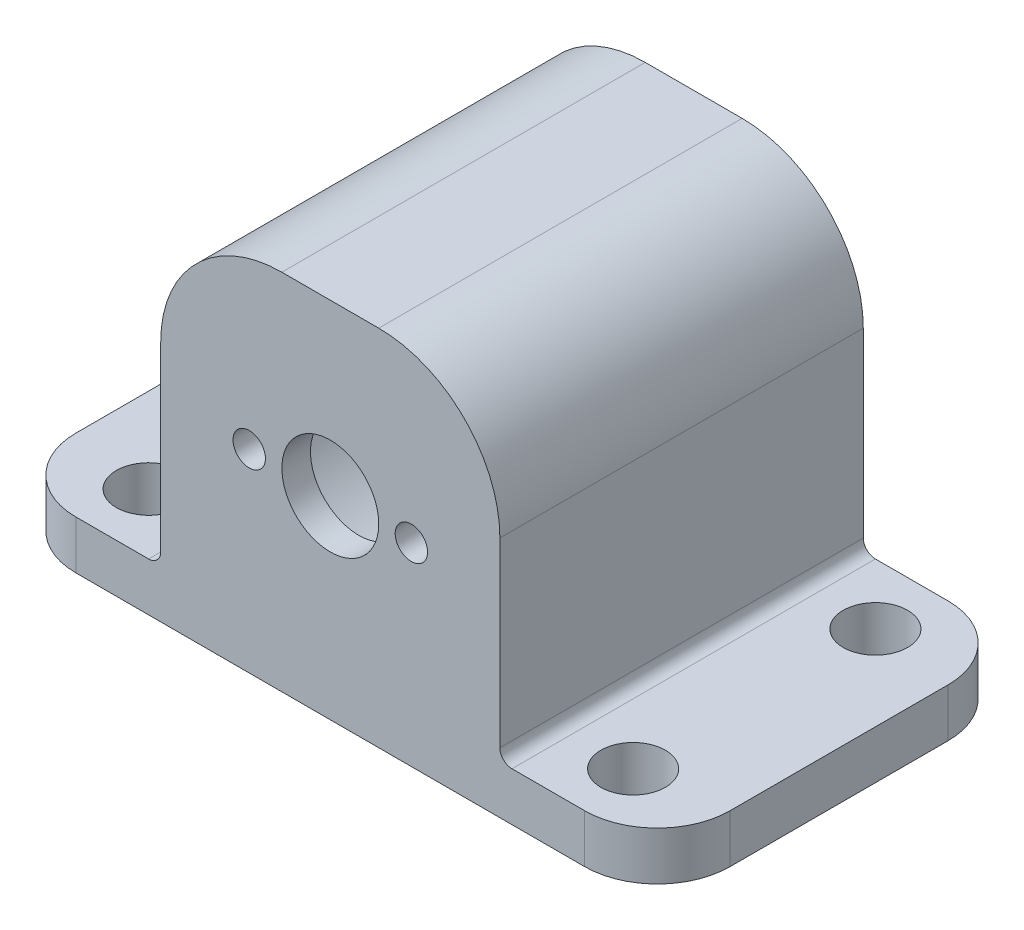
SolidWorks part; units mm, degrees
ref_plane "Front Plane" through (0, 0, 0) normal (0, 0, 1) x (1, 0, 0)
ref_plane "Top Plane" through (0, 0, 0) normal (0, 1, 0) x (1, 0, 0)
ref_plane "Right Plane" through (0, 0, 0) normal (1, 0, 0) x (0, 0, -1)
sketch "Sketch1" plane through (0, 0, 0) normal (0, 0, 1) x (1, 0, 0)
  line L0 (-34.29, 0) -> (34.29, 0)
  line L1 (34.29, 0) -> (34.29, 5.08)
  line L2 (34.29, 5.08) -> (19.05, 5.08)
  line L3 (17.78, 6.35) -> (17.78, 20.32)
  line L5 (0, 6.35) -> (0, 0)
  line L6 (-34.29, 5.08) -> (-19.05, 5.08)
  line L7 (-34.29, 0) -> (-34.29, 5.08)
  line L9 (-17.78, 6.35) -> (-17.78, 20.32)
  line L12 (-17.78, 20.32) -> (-17.78, 25.4)
  line L13 (-5.08, 38.1) -> (5.08, 38.1)
  line L14 (17.78, 20.32) -> (17.78, 25.4)
  arc A0 (-14.224, 20.32) -> (14.224, 20.32) centre (0, 20.32) ccw
  circle A1 centre (0, 20.32) radius 14.224
  arc A2 (-5.08, 38.1) -> (-17.78, 25.4) centre (-5.08, 25.4) ccw
  arc A3 (17.78, 25.4) -> (5.08, 38.1) centre (5.08, 25.4) ccw
  arc A4 (19.05, 5.08) -> (17.78, 6.35) centre (19.05, 6.35) cw
  arc A5 (-19.05, 5.08) -> (-17.78, 6.35) centre (-19.05, 6.35) ccw
  point P23 (17.78, 5.08)
  point P26 (-17.78, 5.08)
  dimension "D3" = 28.448
  dimension "D6" = 38.1
  dimension "D7" = 12.7
  dimension "D8" = 12.7
  dimension "D9" = 1.27
  dimension "D1" = 34.29
  dimension "D2" = 5.08
  dimension "D4" = 20.32
  dimension "D5" = 17.78
extrude "Boss-Extrude1" add sketch "Sketch1" along normal blind 38.1 contours A0 A1 | L9 L12 A2 L13 A3 L14 L3 A4 L2 L1 L0 L7 L6 A5
hole_wizard "1/4 Clearance Hole1" positions "Sketch2" profile "Sketch3" hole size "1/4" standard "ANSI Inch" end condition through all
sketch "Sketch2" plane through (0, 5.08, 0) normal (0, 1, 0) x (1, 0, 0)
  line L0 (-34.29, -19.05) -> (34.29, -19.05) construction
  line L1 (-34.29, -38.1) -> (-34.29, 0) construction
  line L2 (34.29, -38.1) -> (34.29, 0) construction
  line L7 (0, 0) -> (0, -38.1) construction
  line L8 (-5.08, -38.1) -> (5.08, -38.1) construction
  point P0 (-25.4, -6.35)
  point P37 (25.4, -31.75)
  point P43 (-25.4, -31.75)
  point P45 (25.4, -6.35)
  dimension "D1" = 25.4
  dimension "D2" = 12.7
  dimension "D7" = 12.7
  dimension "D8" = 25.4
sketch "Sketch3" plane through (-25.4, 5.08, 6.35) normal (1, 0, 0) x (0, 0, 1)
  line L0 (0, 0) -> (0, 5.08)
  line L1 (0, 5.08) -> (3.3782, 5.08)
  line L2 (3.3782, 5.08) -> (3.3782, 0)
  line L5 (3.3782, 0) -> (0, 0)
  line L11 (0, -6.35) -> (0, 107.95) construction
  dimension "Thru Hole Dia." = 6.7564
  dimension "Thru Hole Depth" = 5.08
sketch "Sketch4" plane through (0, 0, 38.1) normal (0, 0, 1) x (1, 0, 0)
  circle A0 centre (0, 20.32) radius 16.6372
  circle A1 centre (0, 20.32) radius 5.08
  circle A2 centre (8.5, 20.32) radius 1.7
  circle A3 centre (-8.5, 20.32) radius 1.7
  dimension "D1" = 3.4
  dimension "D2" = 3.4
  dimension "D5" = 10.16
  dimension "D3" = 8.5
  dimension "D4" = 8.5
extrude "Boss-Extrude2" add sketch "Sketch4" against normal blind 3
fillet "Fillet1" radius 7.62 4 edges at (34.29, 2.54, 0) (34.29, 2.54, 38.1) (-34.29, 2.54, 38.1) (-34.29, 2.54, 0)
chamfer "Chamfer1" distance 1.27 angle 45 1 edges at (14.224, 20.32, 0)
